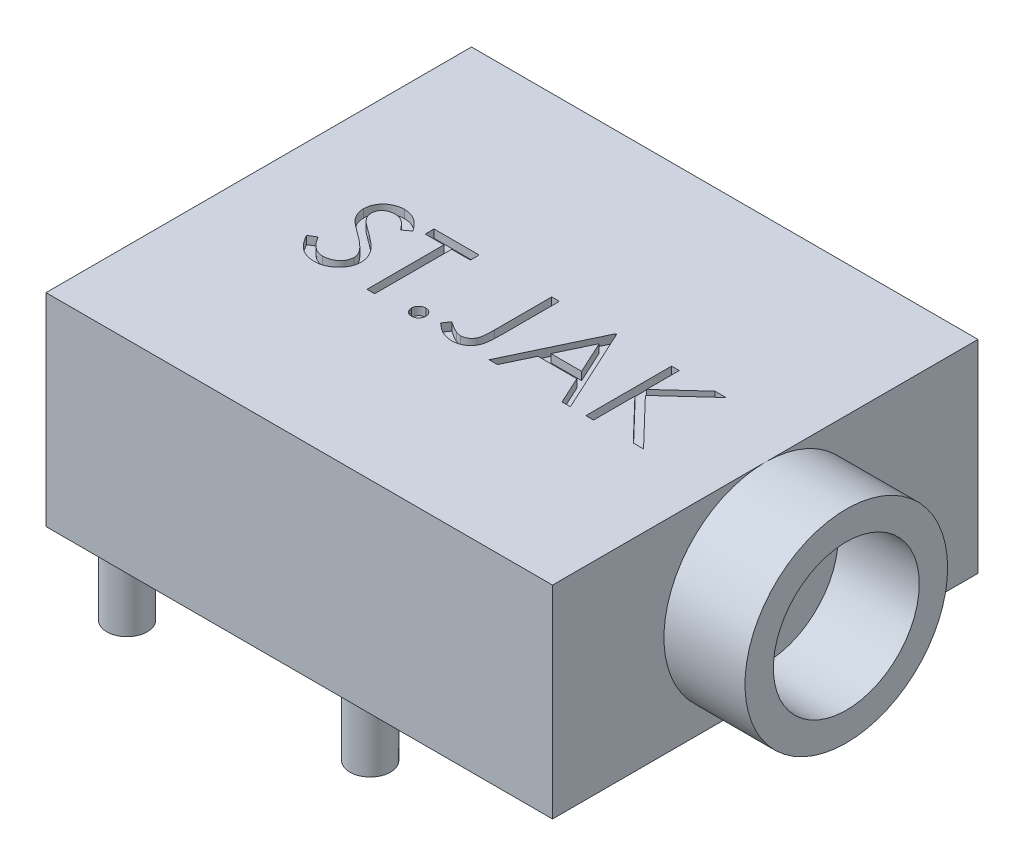
SolidWorks part; units mm, degrees
ref_plane "Front Plane" through (0, 0, 0) normal (0, 0, 1) x (1, 0, 0)
ref_plane "Top Plane" through (0, 0, 0) normal (0, 1, 0) x (1, 0, 0)
ref_plane "Right Plane" through (0, 0, 0) normal (1, 0, 0) x (0, 0, -1)
sketch "Sketch1" plane through (0, 0, 0) normal (0, 1, 0) x (1, 0, 0)
  line L1 (-1, -1) -> (11.5, -1)
  line L2 (-1, -1) -> (-1, 9.5)
  line L3 (-1, 9.5) -> (11.5, 9.5)
  line L4 (11.5, -1) -> (11.5, 9.5)
extrude "Extrude1" add sketch "Sketch1" along normal blind 5
sketch "Sketch2" plane through (0, 0, 0) normal (0, -1, 0) x (1, 0, 0)
  line L0 (0, 0) -> (10.9823, 0) construction
  line L1 (0, 0) -> (0, -8.449) construction
  line L2 (4, 0) -> (4, -8.449) construction
  line L3 (-1.3389, -8.5) -> (9.4603, -8.5) construction
  line L4 (6, 0) -> (6, -8.5) construction
  line L6 (8.5, 0) -> (8.5, -8.5) construction
  circle A0 centre (0, 0) radius 0.5
  circle A1 centre (6, 0) radius 0.5
  circle A2 centre (0, -8.5) radius 0.5
  circle A3 centre (4, -8.5) radius 0.5
  circle A4 centre (8.5, -8.5) radius 0.5
  dimension "D1" = 4
  dimension "D2" = 6
  dimension "D3" = 8.5
  dimension "D4" = 4.5
extrude "Extrude2" add sketch "Sketch2" along normal blind 2
sketch "Sketch3" plane through (11.5, 0, 0) normal (1, 0, 0) x (0, 0, -1)
  circle A0 centre (4.25, 2.5) radius 2.5
  circle A1 centre (4.25, 2.5) radius 1.8
extrude "Extrude3" add sketch "Sketch3" along normal blind 2
sketch "Sketch4" plane through (0, 5, 0) normal (0, 1, 0) x (1, 0, 0)
  line L0 (0.9354, 3.032) -> (8.9028, 3.032) construction
  text T0 "ST.JAK" font "Century Gothic" height in points 8
extrude "Extrude4" cut sketch "Sketch4" against normal blind 0.2
